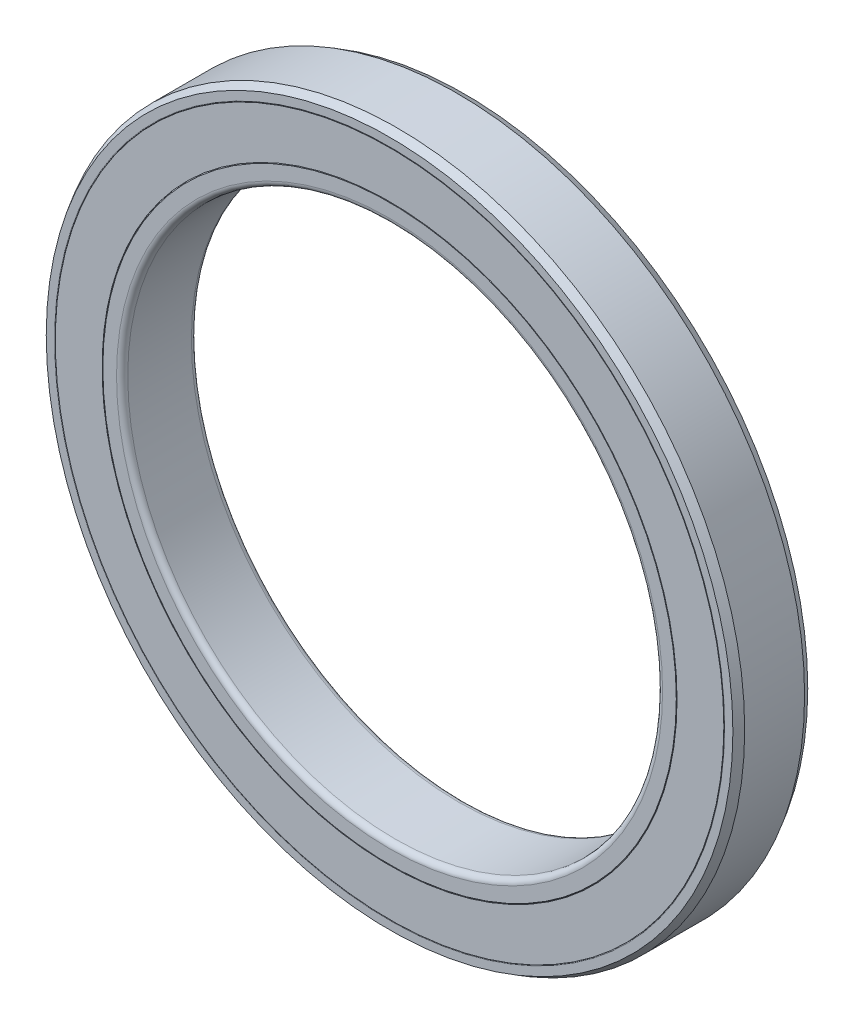
SolidWorks part; units mm, degrees
material "Plain Carbon Steel"
ref_plane "Front Plane" through (0, 0, 0) normal (0, 0, 1) x (1, 0, 0)
ref_plane "Top Plane" through (0, 0, 0) normal (0, 1, 0) x (1, 0, 0)
ref_plane "Right Plane" through (0, 0, 0) normal (1, 0, 0) x (0, 0, -1)
sketch "Sketch1" plane through (0, 0, 0) normal (0, 0, 1) x (1, 0, 0)
  line L0 (0, 28.75) -> (0, 32.5) construction
  line L1 (0, 25) -> (0, 28.75) construction
  line L2 (0, 32.5) -> (0, 31.25) construction
  line L3 (0, 31.25) -> (0, 30) construction
  line L4 (0, 30) -> (0, 28.75) construction
  circle A0 centre (0, 0) radius 25
  circle A1 centre (0, 0) radius 32.5
  circle A2 centre (0, 0) radius 31.25 construction
  circle A4 centre (0, 0) radius 26.875 construction
  point P6 (0, 26.875)
  dimension "OD" = 65
  dimension "ID" = 50
sketch "Sketch2" plane through (0, 0, 0) normal (1, 0, 0) x (0, 0, -1)
  line L0 (-3.5, 32.5) -> (3.5, 32.5) construction
  line L1 (3.5, 32.5) -> (3.5, -32.5) construction
  line L2 (3.5, 0) -> (-3.5, 0) construction
  line L3 (-3.5, 25) -> (-3.5, -25) construction
  point P2 (0, 32.5)
  dimension "Width" = 7
  dimension "For Shaft Diameter" = 50
  dimension "For Housing ID" = 65
sketch "Sketch3" plane through (0, 0, 0) normal (1, 0, 0) x (0, 0, -1)
  line L0 (-2.8, -32.5) -> (2.8, -32.5)
  line L3 (-3.5, -31.32) -> (-3.5, -32.0959)
  line L4 (0, -26.875) -> (0, -31.25) construction
  line L5 (-2.8, -32.5) -> (-3.5, -32.0959)
  line L6 (-2.975, -25) -> (2.975, -25)
  line L7 (-2.0833, -31.25) -> (-2.0833, -31.6667) construction
  line L8 (-3.43, -26.875) -> (-2.0833, -26.875)
  line L9 (-3.5, -26.875) -> (0, -26.875) construction
  line L11 (-3.5, -31.25) -> (-3.5, -26.875) construction
  line L12 (-3.5, -26.805) -> (-3.5, -25.525)
  line L14 (-3.5, 0) -> (3.5, 0) construction
  line L15 (-3.43, -31.25) -> (-2.0833, -31.25)
  line L17 (0, 0) -> (0, -32.5) construction
  line L18 (-2.0833, -31.6667) -> (-2.0833, -32.0833) construction
  line L19 (2.8, -32.5) -> (3.5, -32.0959)
  line L20 (0, -31.25) -> (-3.5, -31.25) construction
  line L21 (-3.5, 25) -> (-3.5, -25) construction
  line L22 (-2.0833, -32.0833) -> (-2.0833, -32.5) construction
  line L30 (-3.5, -26.805) -> (-3.43, -26.875)
  line L31 (3.43, -26.875) -> (2.0833, -26.875)
  line L32 (3.5, -26.805) -> (3.43, -26.875)
  line L33 (3.5, -26.805) -> (3.5, -25.525)
  line L34 (3.43, -31.25) -> (2.0833, -31.25)
  line L35 (3.5, -31.32) -> (3.5, -32.0959)
  line L36 (0, 32.5) -> (0, -32.5) construction
  arc A0 (0, -26.0417) -> (0, -32.0833) centre (0, -29.0625) ccw construction
  arc A1 (-2.0833, -26.875) -> (2.0833, -26.875) centre (0, -29.0625) cw
  arc A2 (-2.0833, -31.25) -> (2.0833, -31.25) centre (0, -29.0625) ccw
  arc A4 (-3.43, -31.25) -> (-3.5, -31.32) centre (-3.43, -31.32) ccw
  arc A5 (-2.975, -25) -> (-3.5, -25.525) centre (-2.975, -25.525) ccw
  arc A6 (2.975, -25) -> (3.5, -25.525) centre (2.975, -25.525) cw
  arc A7 (3.43, -31.25) -> (3.5, -31.32) centre (3.43, -31.32) cw
  point P28 (0, -29.0625)
  point P46 (-3.5, -25)
  point P54 (0, -25)
  dimension "D4" = 0.07
  dimension "D7" = 0.525
  dimension "D5" = 45
  dimension "D6" = 0.07
  dimension "D3" = 0.7
  dimension "D2" = 60
revolve "Revolve1" add sketch "Sketch3" angle 360 about L14
sketch "Sketch4" plane through (0, 0, 0) normal (1, 0, 0) x (0, 0, -1)
  line L0 (-3.43, -31.25) -> (-2.0833, -31.25) construction
  line L1 (-3.5, -26.875) -> (-3.1406, -26.875)
  line L2 (-3.5, -26.875) -> (-3.5, -31.25)
  line L3 (-3.5, -31.25) -> (-3.1406, -31.25)
  line L4 (-3.1406, -26.875) -> (-3.1406, -31.25)
  line L5 (-3.5, -26.805) -> (-3.5, -25.525) construction
  line L6 (-3.5, -29.0625) -> (-3.3802, -29.0625) construction
  line L7 (-3.3802, -29.0625) -> (-3.2604, -29.0625) construction
  line L8 (-3.2604, -29.0625) -> (-3.1406, -29.0625) construction
  line L9 (-3.1406, -29.0625) -> (-3.0208, -29.0625) construction
  line L10 (-3.5, -31.25) -> (-3.5, -26.875) construction
  line L11 (-3.43, -26.875) -> (-2.0833, -26.875) construction
  arc A1 (0, -26.0417) -> (0, -32.0833) centre (0, -29.0625) ccw construction
revolve "Revolve2" add sketch "Sketch4" angle 360 about L14
sketch "Sketch5" plane through (0, 0, 0) normal (1, 0, 0) x (0, 0, -1)
  line L2 (0, -26.0417) -> (0, -32.0833)
  arc A2 (0, -32.0833) -> (0, -26.0417) centre (0, -29.0625) cw
revolve "Revolve3" add sketch "Sketch5" angle 360 about L17
pattern_circular "CirPattern1" count 7 over 360 about axis through (0, 0, 0) along (0, 0, 1) of bodies 138
equation "\"D4@Sketch3\"=\"Width@Sketch2\"*.01"
equation "\"D6@Sketch3\"=\"Width@Sketch2\"*.01"
equation "\"D7@Sketch3\"=\"Width@Sketch2\"*.075"
equation "\"D3@Sketch3\"=\"Width@Sketch2\"*.1"
